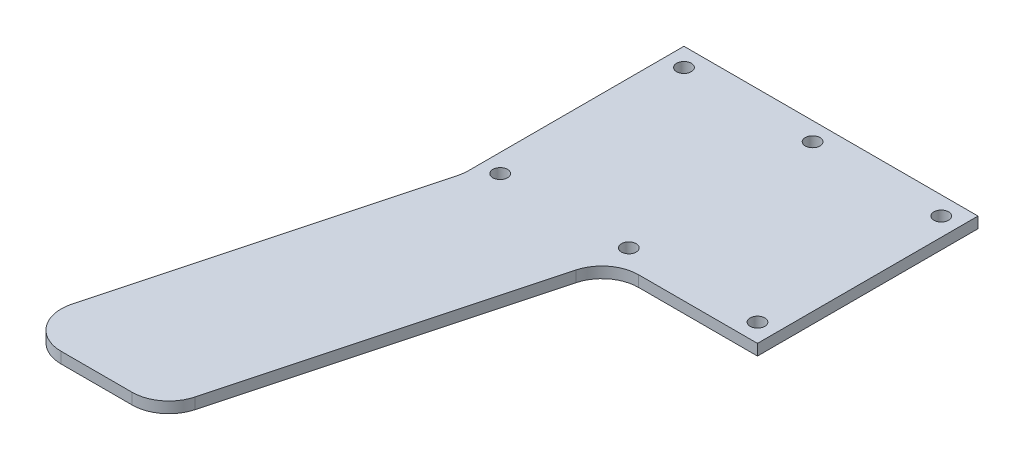
SolidWorks part; units mm, degrees
ref_plane "Front Plane" through (0, 0, 0) normal (0, 0, 1) x (1, 0, 0)
ref_plane "Top Plane" through (0, 0, 0) normal (0, 1, 0) x (1, 0, 0)
ref_plane "Right Plane" through (0, 0, 0) normal (1, 0, 0) x (0, 0, -1)
sketch "Sketch1" plane through (0, 0, 0) normal (0, 1, 0) x (1, 0, 0)
  line L0 (40, 0) -> (14.1181, -96.5926)
  line L1 (0, 0) -> (80, 0)
  line L2 (0, 0) -> (0, 60)
  line L3 (0, 60) -> (80, 60)
  line L4 (80, 0) -> (80, 60)
  line L5 (0, 0) -> (-25.8819, -96.5926)
  line L6 (-25.8819, -96.5926) -> (14.1181, -96.5926)
  circle A0 centre (5, 55) radius 2
  circle A1 centre (75, 55) radius 2
  circle A2 centre (75, 5) radius 2
  circle A3 centre (5, 5) radius 2
  circle A4 centre (40, 55) radius 2
  circle A5 centre (40, 5) radius 2
  dimension "D5" = 4
  dimension "D8" = 4
  dimension "D9" = 4
  dimension "D10" = 4
  dimension "D11" = 4
  dimension "D12" = 4
  dimension "D13" = 5
  dimension "D14" = 5
  dimension "D15" = 5
  dimension "D16" = 5
  dimension "D17" = 5
  dimension "D18" = 5
  dimension "D19" = 5
  dimension "D20" = 5
  dimension "D21" = 5
  dimension "D22" = 40
  dimension "D23" = 40
  dimension "D24" = 5
  dimension "D1" = 80
  dimension "D2" = 60
  dimension "D3" = 40
  dimension "D4" = 75
  dimension "D6" = 100
  dimension "D7" = 100
extrude "Boss-Extrude1" add sketch "Sketch1" along normal blind 3 contours L1 L4 L3 L2 A5 A4 A3 A2 A1 A0 | L5 L6 L0 L1
fillet "Fillet1" radius 10 4 edges at (40, 1.5, 0) (0, 1.5, 0) (-25.8819, 1.5, 96.5926) (14.1181, 1.5, 96.5926)
